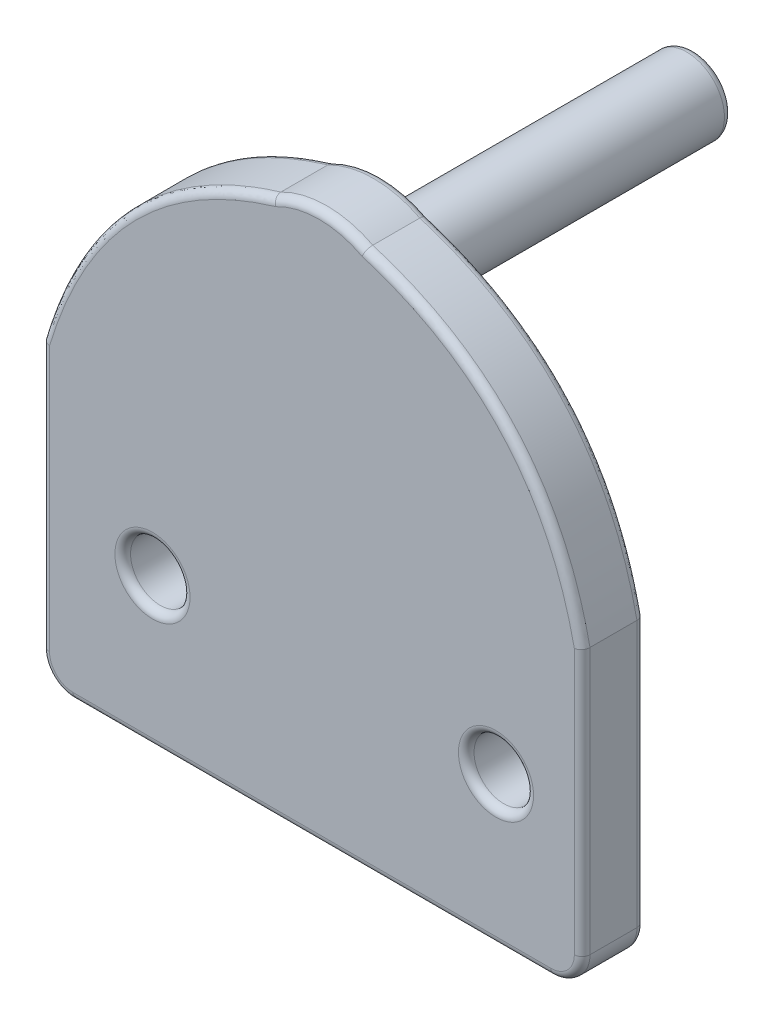
SolidWorks part; units mm, degrees
ref_plane "Front Plane" through (0, 0, 0) normal (0, 0, 1) x (1, 0, 0)
ref_plane "Top Plane" through (0, 0, 0) normal (0, 1, 0) x (1, 0, 0)
ref_plane "Right Plane" through (0, 0, 0) normal (1, 0, 0) x (0, 0, -1)
sketch "Sketch1" plane through (0, 0, 0) normal (0, 0, 1) x (1, 0, 0)
  line L2 (66.3701, 9.5) -> (66.3701, -7.5)
  line L3 (68.3701, -9.5) -> (98.8957, -9.5)
  line L4 (100.8957, 9.5) -> (100.8957, -7.5)
  circle A0 centre (73.4455, 0) radius 1.9
  arc A1 (87.0249, 24.8198) -> (81.146, 24.8198) centre (84.0854, 19.1348) ccw
  circle A2 centre (95.3891, 0) radius 1.9
  arc A3 (66.3701, -7.5) -> (68.3701, -9.5) centre (68.3701, -7.5) ccw
  arc A4 (98.8957, -9.5) -> (100.8957, -7.5) centre (98.8957, -7.5) ccw
  spline S0 degree 2 poles (87.0249, 24.8198) (98.4256, 21.3305) (100.8957, 9.5) knots 0 0 0 1 1 1
  spline S1 degree 2 poles (81.146, 24.8198) (69.9439, 21.4566) (66.3701, 9.5) knots 0 0 0 1 1 1
extrude "Boss-Extrude1" add sketch "Sketch1" along normal blind 4
sketch "Sketch2" plane through (0, 0, 0) normal (0, 0, -1) x (-1, 0, 0)
  circle A0 centre (-84.0854, 20.1328) radius 2.4
  point P2 (0, 0)
  point P3 (-84.0854, 19.1348)
  point P4 (-84.0854, 20.1328)
extrude "Boss-Extrude2" add sketch "Sketch2" along normal blind 20
fillet "Fillet1" radius 1 1 edges at (86.4854, 20.1328, 0)
fillet "Fillet2" radius 0.5 1 edges at (81.6854, 20.1328, -20)
fillet "Fillet3" radius 0.5 20 edges at (75.3455, 0, 0) (97.2891, 0, 0) (84.0854, 25.5348, 0) (66.3701, 1, 0) (66.9559, -8.9142, 0) (83.6329, -9.5, 0) (100.3099, -8.9142, 0) (100.8957, 1, 0) (75.3455, 0, 4) (100.8957, 1, 4) (100.3099, -8.9142, 4) (83.6329, -9.5, 4) (66.9559, -8.9142, 4) (66.3701, 1, 4) (84.0854, 25.5348, 4) (97.2891, 0, 4)
